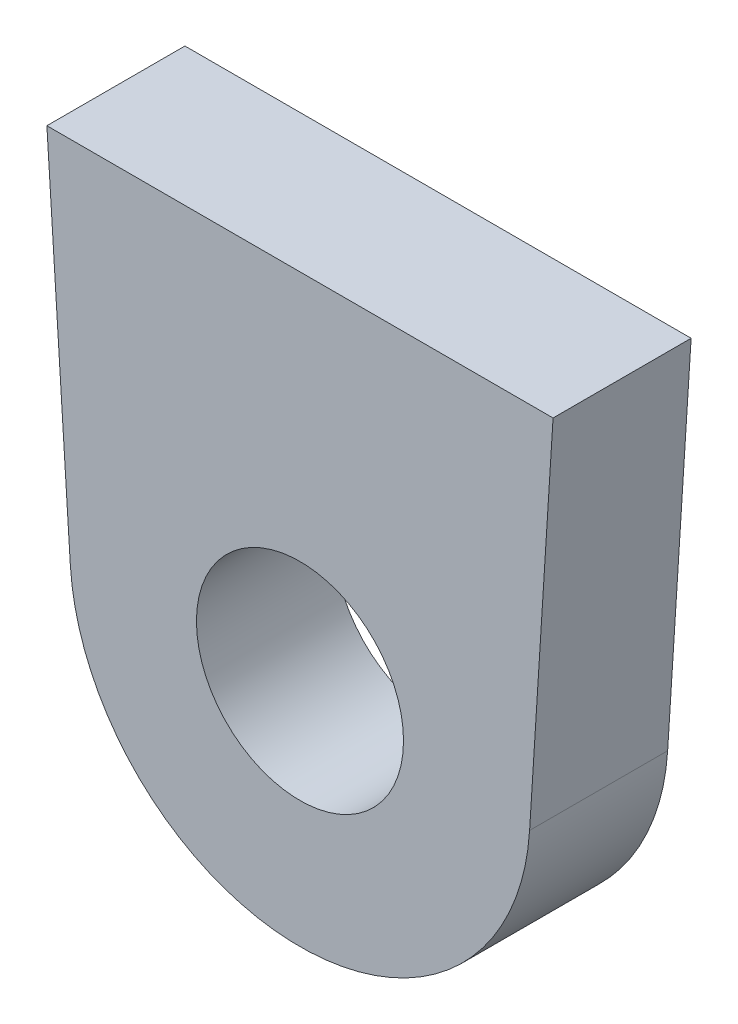
SolidWorks part; units mm, degrees
ref_plane "前视基准面" through (0, 0, 0) normal (0, 0, 1) x (1, 0, 0)
ref_plane "上视基准面" through (0, 0, 0) normal (0, 1, 0) x (1, 0, 0)
ref_plane "右视基准面" through (0, 0, 0) normal (1, 0, 0) x (0, 0, -1)
sketch "草图1" plane through (0, 0, 0) normal (0, 0, 1) x (1, 0, 0)
  line L0 (-55, 77) -> (55, 77)
  line L1 (-55, 77) -> (-49.8991, -3.1747)
  line L2 (55, 77) -> (49.8991, -3.1747)
  circle A0 centre (0, 0) radius 22.5
  arc A1 (-49.8991, -3.1747) -> (49.8991, -3.1747) centre (0, 0) ccw
  point P6 (0, 77)
  dimension "D1" = 77
  dimension "D2" = 100
  dimension "D3" = 45
  dimension "D4" = 110
extrude "凸台-拉伸1" add sketch "草图1" along normal blind 30
